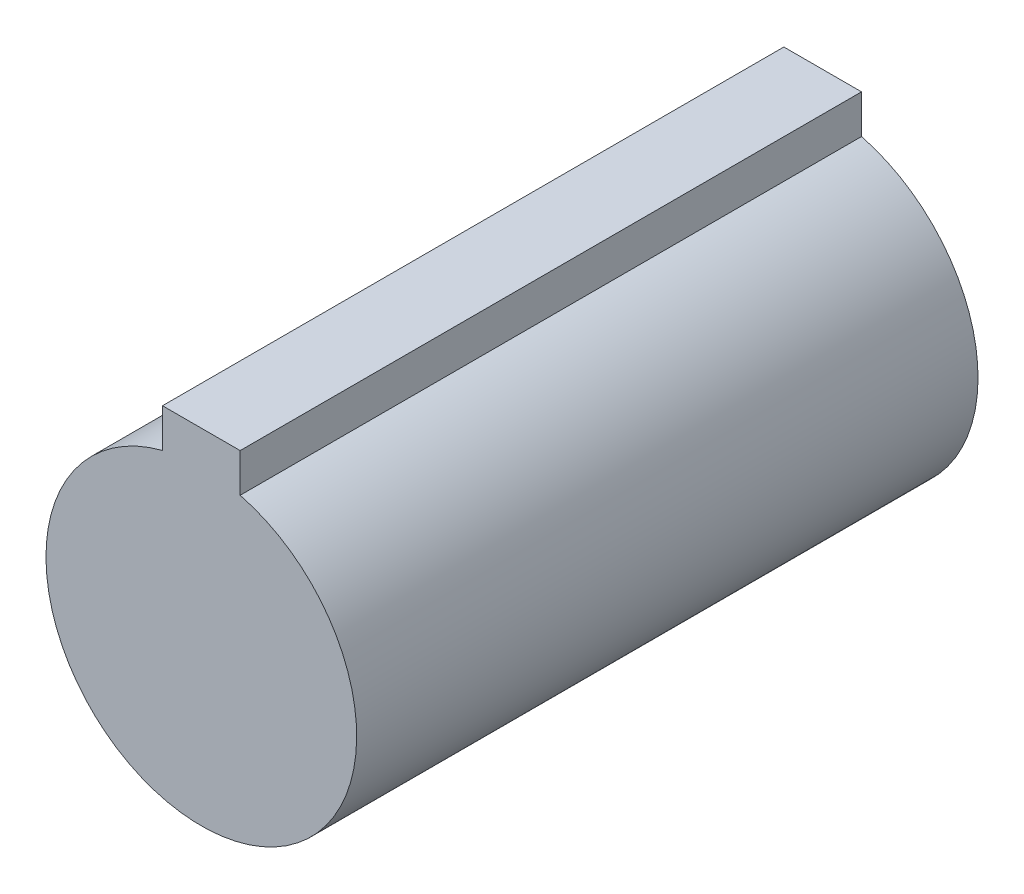
SolidWorks part; units mm, degrees
ref_plane "Front Plane" through (0, 0, 0) normal (0, 0, 1) x (1, 0, 0)
ref_plane "Top Plane" through (0, 0, 0) normal (0, 1, 0) x (1, 0, 0)
ref_plane "Right Plane" through (0, 0, 0) normal (1, 0, 0) x (0, 0, -1)
sketch "Sketch2" plane through (0, 0, 25.4) normal (0, 0, 1) x (1, 0, 0)
  line L0 (-1.806, 2.5317) -> (-1.806, 11.6599) construction
  line L2 (-3.3935, 10.2632) -> (-0.2185, 10.2632)
  line L3 (-3.3935, 10.2632) -> (-3.3935, 8.6757)
  line L4 (-3.3935, 8.6757) -> (-0.2185, 8.6757)
  line L5 (-0.2185, 10.2632) -> (-0.2185, 8.6757)
  line L6 (-3.3935, 10.2632) -> (-0.2185, 8.6757) construction
  line L7 (-3.3935, 8.6757) -> (-0.2185, 10.2632) construction
  circle A0 centre (-1.806, 2.5317) radius 6.35
  point P3 (-1.806, 9.4694)
  dimension "D1" = 12.7
  dimension "D2" = 1.5875
  dimension "D3" = 3.175
extrude "Boss-Extrude2" add sketch "Sketch2" along normal blind 25.4
sketch "Sketch5" plane through (0, 0, 50.8) normal (0, 0, 1) x (1, 0, 0)
